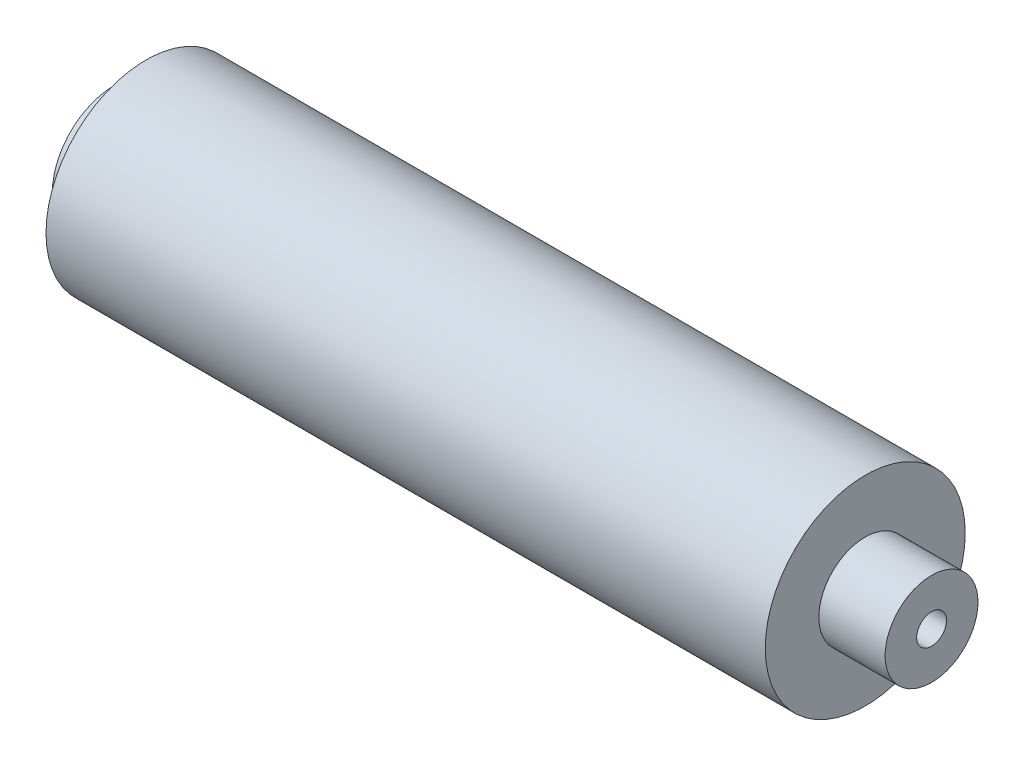
SolidWorks part; units mm, degrees
ref_plane "Front Plane" through (0, 0, 0) normal (0, 0, 1) x (1, 0, 0)
ref_plane "Top Plane" through (0, 0, 0) normal (0, 1, 0) x (1, 0, 0)
ref_plane "Right Plane" through (0, 0, 0) normal (1, 0, 0) x (0, 0, -1)
sketch "Sketch1" plane through (0, 0, 0) normal (1, 0, 0) x (0, 0, -1)
  circle A0 centre (0, 0) radius 15.0762
  dimension "D1" = 30.1523
extrude "Boss-Extrude1" add sketch "Sketch1" along normal blind 118.4446
sketch "Sketch2" plane through (0, 0, 0) normal (-1, 0, 0) x (0, 0, 1)
  circle A0 centre (0, 0) radius 4.5847
  circle A1 centre (0, 0) radius 9.3853
  dimension "D1" = 18.7706
  dimension "D2" = 9.1694
extrude "Boss-Extrude2" add sketch "Sketch2" along normal blind 4.7498
sketch "Sketch3" plane through (118.4446, 0, 0) normal (1, 0, 0) x (0, 0, -1)
  line L0 (-1.8708, 1.25) -> (1.8708, 1.25)
  line L1 (-1.8708, 1.25) -> (0, -2.25) construction
  line L2 (0, -2.25) -> (1.8708, 1.25) construction
  line L3 (0, -2.25) -> (0, 1.25) construction
  arc A0 (-1.8708, 1.25) -> (1.8708, 1.25) centre (0, 0) ccw
  dimension "D1" = 4.5
  dimension "D2" = 3.5
extrude "Cut-Extrude1" cut sketch "Sketch3" against normal blind 26
sketch "Sketch4" plane through (118.4446, 0, 0) normal (1, 0, 0) x (0, 0, -1)
  circle A0 centre (0, 0) radius 2.25
  arc A1 (-1.8708, 1.25) -> (1.8708, 1.25) centre (0, 0) ccw construction
extrude "Cut-Extrude2" cut sketch "Sketch4" against normal blind 2.6
sketch "Sketch5" plane through (118.4446, 0, 0) normal (1, 0, 0) x (0, 0, -1)
  circle A0 centre (0, 0) radius 7
  circle A1 centre (0, 0) radius 15.0762
  circle A2 centre (0, 0) radius 15.0762 construction
  dimension "D1" = 14
extrude "Cut-Extrude3" cut sketch "Sketch5" against normal blind 10
